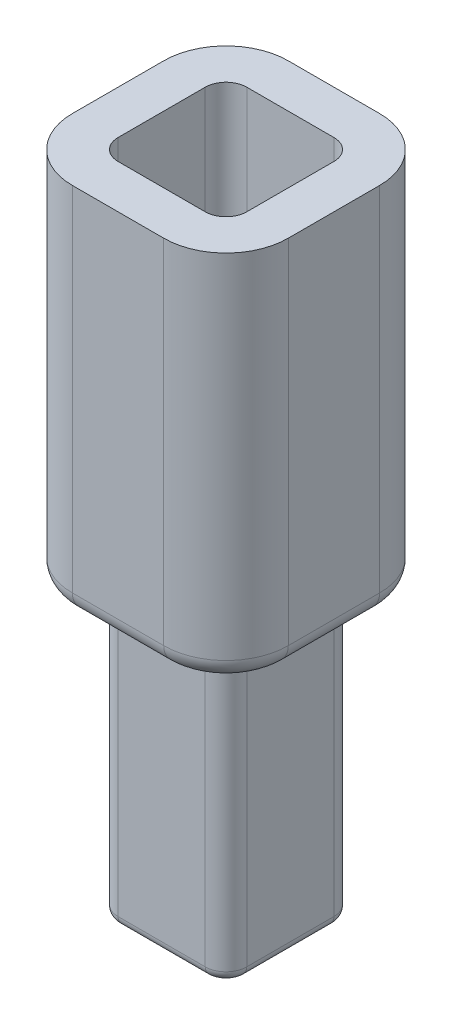
SolidWorks part; units mm, degrees
ref_plane "Front Plane" through (0, 0, 0) normal (0, 0, 1) x (1, 0, 0)
ref_plane "Top Plane" through (0, 0, 0) normal (0, 1, 0) x (1, 0, 0)
ref_plane "Right Plane" through (0, 0, 0) normal (1, 0, 0) x (0, 0, -1)
sketch "Sketch1" plane through (0, 0, 0) normal (0, 1, 0) x (1, 0, 0)
  line L1 (-2.1, 3.1) -> (2.1, 3.1)
  line L2 (-3.1, 2.1) -> (-3.1, -2.1)
  line L3 (-2.1, -3.1) -> (2.1, -3.1)
  line L4 (3.1, 2.1) -> (3.1, -2.1)
  line L5 (-3.1, 3.1) -> (3.1, -3.1) construction
  line L6 (-3.1, -3.1) -> (3.1, 3.1) construction
  arc A0 (2.1, -3.1) -> (3.1, -2.1) centre (2.1, -2.1) ccw
  arc A1 (-3.1, -2.1) -> (-2.1, -3.1) centre (-2.1, -2.1) ccw
  arc A2 (-2.1, 3.1) -> (-3.1, 2.1) centre (-2.1, 2.1) ccw
  arc A3 (2.1, 3.1) -> (3.1, 2.1) centre (2.1, 2.1) cw
  point P0 (0, 0)
  dimension "D3" = 1
  dimension "D1" = 6.2
  dimension "D2" = 6.2
extrude "Boss-Extrude1" add sketch "Sketch1" along normal blind 14
sketch "Sketch2" plane through (0, 14, 0) normal (0, 1, 0) x (1, 0, 0)
  line L1 (-2.2, 5.2) -> (2.2, 5.2)
  line L2 (-5.2, 2.2) -> (-5.2, -2.2)
  line L3 (-2.2, -5.2) -> (2.2, -5.2)
  line L4 (5.2, 2.2) -> (5.2, -2.2)
  line L5 (-5.2, 5.2) -> (5.2, -5.2) construction
  line L6 (-5.2, -5.2) -> (5.2, 5.2) construction
  arc A1 (-5.2, -2.2) -> (-2.2, -5.2) centre (-2.2, -2.2) ccw
  arc A2 (-2.2, 5.2) -> (-5.2, 2.2) centre (-2.2, 2.2) ccw
  arc A3 (2.2, 5.2) -> (5.2, 2.2) centre (2.2, 2.2) cw
  arc A4 (2.2, -5.2) -> (5.2, -2.2) centre (2.2, -2.2) ccw
  dimension "D1" = 3
  dimension "D2" = 10.4
  dimension "D3" = 10.4
extrude "Boss-Extrude2" add sketch "Sketch2" along normal blind 18
sketch "Sketch3" plane through (0, 32, 0) normal (0, 1, 0) x (1, 0, 0)
  line L1 (-2.1, 3.1) -> (2.1, 3.1)
  line L2 (-3.1, 2.1) -> (-3.1, -2.1)
  line L3 (-2.1, -3.1) -> (2.1, -3.1)
  line L4 (3.1, 2.1) -> (3.1, -2.1)
  line L5 (-3.1, 3.1) -> (3.1, -3.1) construction
  line L6 (-3.1, -3.1) -> (3.1, 3.1) construction
  arc A0 (-3.1, -2.1) -> (-2.1, -3.1) centre (-2.1, -2.1) ccw
  arc A1 (2.1, -3.1) -> (3.1, -2.1) centre (2.1, -2.1) ccw
  arc A2 (2.1, 3.1) -> (3.1, 2.1) centre (2.1, 2.1) cw
  arc A3 (-2.1, 3.1) -> (-3.1, 2.1) centre (-2.1, 2.1) ccw
  point P0 (0, 0)
  dimension "D3" = 1
  dimension "D1" = 6.2
  dimension "D2" = 6.2
extrude "Cut-Extrude1" cut sketch "Sketch3" against normal blind 15
fillet "Fillet4" radius 1 8 edges at (-4.3213, 14, 4.3213) (-5.2, 14, 0) (-4.3213, 14, -4.3213) (0, 14, 5.2) (4.3213, 14, 4.3213) (5.2, 14, 0) (4.3213, 14, -4.3213) (0, 14, -5.2)
fillet "Fillet5" radius 0.5 8 edges at (-2.8071, 0, 2.8071) (-3.1, 0, 0) (-2.8071, 0, -2.8071) (0, 0, -3.1) (2.8071, 0, -2.8071) (3.1, 0, 0) (2.8071, 0, 2.8071) (0, 0, 3.1)
